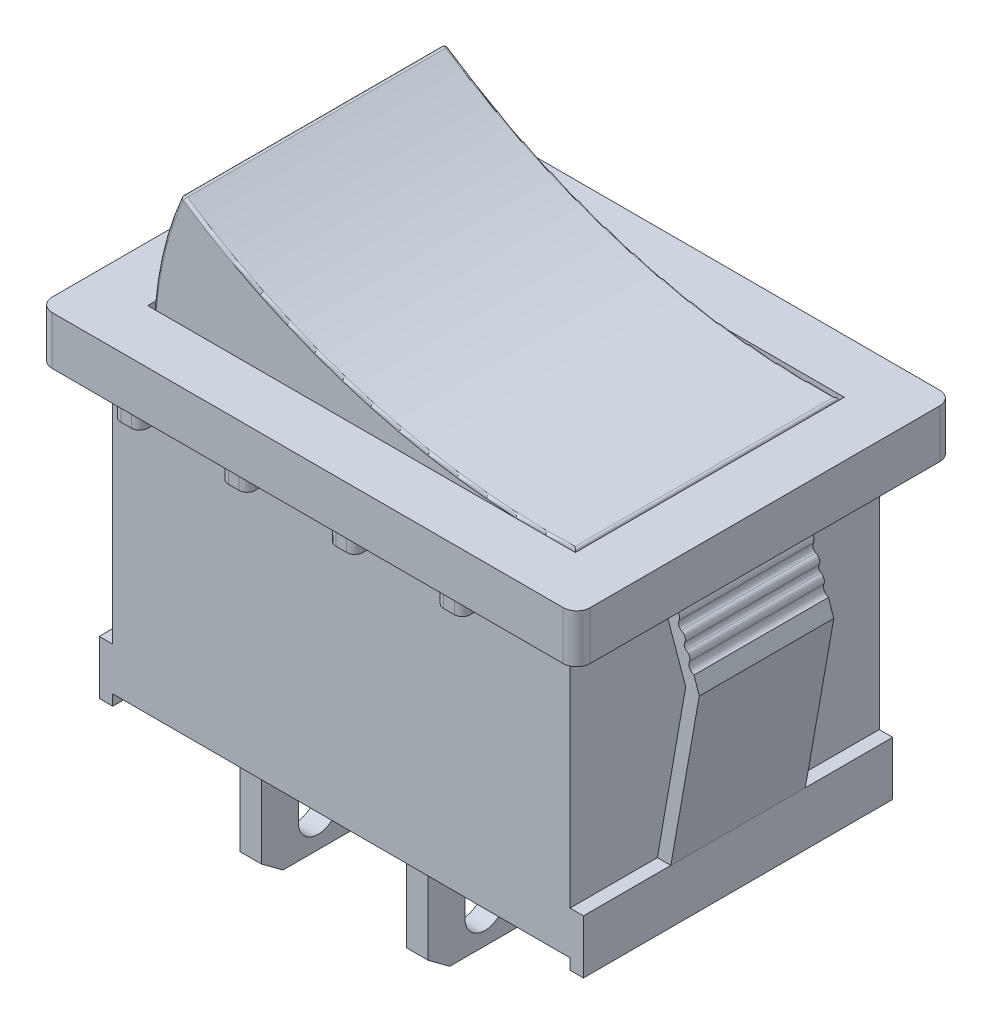
SolidWorks part; units mm, degrees
ref_plane "Front Plane" through (0, 0, 0) normal (0, 0, 1) x (1, 0, 0)
ref_plane "Top Plane" through (0, 0, 0) normal (0, 1, 0) x (1, 0, 0)
ref_plane "Right Plane" through (0, 0, 0) normal (1, 0, 0) x (0, 0, -1)
sketch "Sketch1" plane through (0, 0, 0) normal (0, 0, 1) x (1, 0, 0)
  line L0 (28.8419, 126.2682) -> (196.9257, 126.2682) construction
  line L1 (9.6613, 5.1642) -> (9.6613, 6.9336)
  line L2 (9.6613, 6.9336) -> (-9.9374, 6.9336)
  line L3 (-9.9374, 6.9336) -> (-9.9374, 5.1642)
  line L4 (-9.9374, 5.1642) -> (-8.8107, 5.1642)
  line L5 (-8.8107, 5.1642) -> (9.6613, 5.1642)
  line L6 (8.1893, 5.1642) -> (8.1893, -3.8358)
  line L7 (8.1893, -3.8358) -> (8.6893, -3.8358)
  line L8 (8.6893, -3.8358) -> (8.6893, -5.8358)
  line L9 (8.6893, -5.8358) -> (8.1893, -5.8358)
  line L10 (8.1893, -5.8358) -> (8.1893, -5.4358)
  line L11 (8.1893, -5.4358) -> (-8.8107, -5.4358)
  line L12 (-8.8107, -5.4358) -> (-8.8107, -5.8358)
  line L13 (-8.8107, -5.8358) -> (-9.3107, -5.8358)
  line L14 (-9.3107, -5.8358) -> (-9.3107, -3.8358)
  line L15 (-9.3107, -3.8358) -> (-8.8107, -3.8358)
  line L16 (-8.8107, -3.8358) -> (-8.8107, 5.1642)
  dimension "D1" = 0.5
  dimension "D2" = 2
  dimension "D3" = 0.4
  dimension "D4" = 9
  dimension "D5" = 17
extrude "Boss-Extrude1" add sketch "Sketch1" along normal blind 11.5 contours L16 L15 L14 L13 L12 L11 L10 L9 L8 L7 L6 L5
sketch "Sketch2" plane through (0, 5.1642, 0) normal (0, 1, 0) x (1, 0, 0)
  line L0 (8.1893, 0) -> (-8.8107, -11.5) construction
  line L1 (-8.8107, 0) -> (8.1893, -11.5) construction
  line L3 (9.6893, 1.25) -> (-10.3107, 1.25)
  line L4 (9.6893, 1.25) -> (9.6893, -12.75)
  line L5 (9.6893, -12.75) -> (-10.3107, -12.75)
  line L6 (-10.3107, 1.25) -> (-10.3107, -12.75)
  line L7 (9.6893, 1.25) -> (-10.3107, -12.75) construction
  line L8 (9.6893, -12.75) -> (-10.3107, 1.25) construction
  point P8 (-0.3107, -5.75)
  dimension "D1" = 20
  dimension "D2" = 14
extrude "Boss-Extrude2" add sketch "Sketch2" along normal blind 1.8
ref_plane "Plane1" through (0, 0, 8.25) normal (0, 0, 1) x (1, 0, 0)
sketch "Sketch3" plane through (0, 0, 8.25) normal (0, 0, 1) x (1, 0, 0)
  line L0 (102.0598, 373.3967) -> (564.7265, 373.3967) construction
  line L1 (8.1893, -3.8358) -> (8.6893, -3.8358)
  line L2 (8.6893, -3.8358) -> (9.7471, 2.1451)
  line L3 (9.7471, 2.1451) -> (9.5488, 2.7255)
  line L4 (8.7298, 5.1039) -> (8.7298, 5.1642)
  line L5 (-10.3107, 5.1642) -> (9.6893, 5.1642) construction
  line L6 (8.7298, 5.1642) -> (8.1893, 5.1642)
  line L7 (8.1893, 5.1642) -> (9.2413, 2.1928)
  line L8 (9.2413, 2.1928) -> (8.1893, -3.8358)
  line L9 (8.6893, -3.8358) -> (8.1893, -3.8358)
  line L10 (-8.8107, -3.8358) -> (-9.3107, -3.8358)
  line L11 (-9.3107, -3.8358) -> (-10.2811, 2.1451)
  line L12 (-10.2811, 2.1451) -> (-10.1179, 2.6658)
  line L13 (-9.403, 4.774) -> (-9.2478, 5.1642)
  line L14 (-9.2478, 5.1642) -> (-8.8107, 5.1642)
  line L15 (-8.8107, 5.1642) -> (-9.7685, 2.1928)
  line L16 (-9.7685, 2.1928) -> (-8.8107, -3.8358)
  arc A0 (9.5488, 2.7255) -> (9.3748, 3.062) centre (9.63, 2.9807) cw
  arc A1 (9.3748, 3.062) -> (9.2685, 3.3731) centre (9.166, 3.1644) ccw
  arc A2 (9.2685, 3.3731) -> (9.2154, 3.6229) centre (9.3668, 3.5245) cw
  arc A3 (9.2154, 3.6229) -> (9.0821, 3.9182) centre (9.001, 3.7039) ccw
  arc A4 (9.0821, 3.9182) -> (9.001, 4.2057) centre (9.1853, 4.1025) cw
  arc A5 (9.001, 4.2057) -> (8.8584, 4.5218) centre (8.7716, 4.2924) ccw
  arc A6 (8.8584, 4.5218) -> (8.8388, 4.8373) centre (9.0063, 4.6893) cw
  arc A7 (8.8388, 4.8373) -> (8.7298, 5.1039) centre (8.6267, 4.9061) ccw
  arc A8 (-10.1179, 2.6658) -> (-9.9427, 3.1176) centre (-10.2562, 2.9793) ccw
  arc A9 (-9.9427, 3.1176) -> (-9.746, 3.4104) centre (-9.6979, 3.1656) cw
  arc A10 (-9.746, 3.4104) -> (-9.746, 3.7039) centre (-9.8927, 3.5571) ccw
  arc A11 (-9.746, 3.7039) -> (-9.5582, 3.9706) centre (-9.5187, 3.7434) cw
  arc A12 (-9.5582, 3.9706) -> (-9.605, 4.2402) centre (-9.7164, 4.082) ccw
  arc A13 (-9.605, 4.2402) -> (-9.3775, 4.5218) centre (-9.1172, 4.0788) cw
  arc A14 (-9.3775, 4.5218) -> (-9.403, 4.774) centre (-9.4558, 4.6412) ccw
extrude "Boss-Extrude3" add sketch "Sketch3" against normal blind 5 contours A6 A7 L4 L6 L7 L8 L1 L2 L3 A0 A1 A2 A3 A4 A5 | L16 L10 L11 L12 A8 A9 A10 A11 A12 A13 A14 L13 L14 L15
ref_plane "Plane2" through (-7.7107, 0, 0) normal (1, 0, 0) x (0, 0, -1)
sketch "Sketch4" plane through (-7.7107, 0, 0) normal (1, 0, 0) x (0, 0, -1)
  line L0 (141.8895, 321.7559) -> (761.8895, 321.7559) construction
  line L1 (-14.9282, -5.3693) -> (5.7399, -5.3693) construction
  line L2 (-4.4696, -12.3753) -> (-3.6704, -11.7743)
  line L3 (-3.6704, -11.7743) -> (-3.6704, -6.7373)
  line L4 (-3.5841, -6.6693) -> (-3.4572, -6.6693)
  line L5 (-3.4572, -6.6693) -> (-3.4572, -5.3693)
  line L6 (-4.4696, -12.3753) -> (-7.0696, -12.3753)
  line L7 (-7.0696, -12.3753) -> (-7.8728, -11.7797)
  line L8 (-7.8728, -11.7797) -> (-7.8728, -6.7427)
  line L9 (-7.9422, -6.6693) -> (-8.0715, -6.6693)
  line L10 (-8.0715, -6.6693) -> (-8.0715, -5.3693)
  line L11 (-8.0715, -5.3693) -> (-3.4572, -5.3693)
  line L12 (-5.7598, -9.5912) -> (-5.7598, -11.1357) construction
  line L13 (-5.0181, -9.5912) -> (-5.0181, -11.1357)
  line L14 (-6.5016, -9.5912) -> (-6.5016, -11.1357)
  arc A0 (-3.6704, -6.7373) -> (-3.5841, -6.6693) centre (-3.5912, -6.749) cw
  arc A1 (-7.8728, -6.7427) -> (-7.9422, -6.6693) centre (-7.9442, -6.7407) ccw
  circle A2 centre (-5.7598, -7.0494) radius 0.9971
  arc A3 (-5.0181, -9.5912) -> (-6.5016, -9.5912) centre (-5.7598, -9.5912) ccw
  arc A4 (-6.5016, -11.1357) -> (-5.0181, -11.1357) centre (-5.7598, -11.1357) ccw
  point P22 (-5.7598, -10.3634)
  point P27 (-5.7598, -11.1357)
  dimension "D1" = 2.6
  dimension "D2" = 1
  dimension "D3" = 1
  dimension "D4" = 1.3
  dimension "D5" = 1.3
extrude "Boss-Extrude4" add sketch "Sketch4" along normal blind 0.8
pattern_linear "LPattern1" count 2 spacing 6.2 along (1, 0, 0) of "Boss-Extrude4"
sketch "Sketch5" plane through (0, 5.1642, 0) normal (0, -1, 0) x (1, 0, 0)
  line L0 (-8.3107, 11.5) -> (-8.3107, 11.7)
  line L1 (-8.8107, 11.5) -> (8.1893, 11.5) construction
  line L2 (-9.3107, 11.5) -> (-9.3107, 0) construction
  line L3 (-7.3107, 11.5) -> (-7.3107, 11.7)
  line L4 (-8.0107, 12) -> (-7.6107, 12)
  line L5 (-7.8107, 12) -> (-7.8107, 11.3092) construction
  line L6 (-8.3107, 11.5) -> (-7.3107, 11.5)
  arc A0 (-7.3107, 11.7) -> (-7.6107, 12) centre (-7.6107, 11.7) ccw
  arc A1 (-8.0107, 12) -> (-8.3107, 11.7) centre (-8.0107, 11.7) ccw
  dimension "D1" = 0.2
  dimension "D2" = 1
  dimension "D3" = 1
  dimension "D4" = 0.4
  dimension "D5" = 0.5
  dimension "D6" = 0.5
extrude "Boss-Extrude5" add sketch "Sketch5" along normal blind 1.2
pattern_linear "LPattern2" count 4 spacing 4 along (1, 0, 0) of "Boss-Extrude5"
sketch "Sketch6" plane through (0, 5.1642, 0) normal (0, -1, 0) x (1, 0, 0)
  line L2 (-0.3107, 5.75) -> (-13.9742, 5.75) construction
  line L3 (-13.9742, 5.75) -> (13.279, 5.75) construction
ref_plane "Plane3" through (0, 0, 5.75) normal (0, 0, 1) x (1, 0, 0)
mirror "Mirror1" about plane through (0, 0, 5.75) normal (0, 0, 1) of "LPattern2", "Boss-Extrude5"
sketch "Sketch7" plane through (0, 6.9642, 0) normal (0, 1, 0) x (1, 0, 0)
  line L0 (-10.3107, -12.75) -> (-0.3107, -5.75) construction
  line L1 (9.6893, 1.25) -> (-10.3107, 1.25) construction
  line L2 (8.1893, -10.75) -> (-8.8107, -10.75)
  line L3 (8.1893, -10.75) -> (8.1893, -0.75)
  line L4 (8.1893, -0.75) -> (-8.8107, -0.75)
  line L5 (-8.8107, -10.75) -> (-8.8107, -0.75)
  line L6 (8.1893, -10.75) -> (-8.8107, -0.75) construction
  line L7 (8.1893, -0.75) -> (-0.3107, -5.75) construction
  line L8 (-10.3107, 1.25) -> (-10.3107, -12.75) construction
  point P2 (-0.3107, -5.75)
  dimension "D1" = 2
  dimension "D2" = 1.5
extrude "Cut-Extrude1" cut sketch "Sketch7" against normal blind 1.5
ref_plane "Plane5" through (0, 0, 0.85) normal (0, 0, 1) x (1, 0, 0)
sketch "Sketch8" plane through (0, 0, 0.85) normal (0, 0, 1) x (1, 0, 0)
  line L0 (-10.3107, 5.1642) -> (-10.3107, 12.8273) construction
  line L1 (9.6893, 5.1642) -> (9.6893, 12.5473) construction
  line L2 (7.5893, 12.3514) -> (7.5893, 3.6168) construction
  line L3 (-8.2107, 12.3514) -> (-8.2107, 3.2529) construction
  line L4 (102.0213, 373.3251) -> (564.688, 373.3251) construction
  line L5 (10.0086, 6.9507) -> (10.0086, 5.4453) construction
  line L6 (10.0086, 5.4453) -> (-15.1054, 5.4453) construction
  line L7 (7.5393, 5.4453) -> (7.5393, 6.9642)
  line L8 (7.5393, 5.4453) -> (-8.1607, 5.4453)
  line L9 (-10.3107, 6.9642) -> (9.6893, 6.9642) construction
  arc A0 (-8.1607, 5.4453) -> (-7.0821, 11.0609) centre (4.4721, 5.9305) cw
  arc A1 (-7.0821, 11.0609) -> (7.5393, 6.9642) centre (6.4773, 31.3145) ccw
  point P22 (0, 0)
  point P25 (7.3979, 6.9507)
  dimension "D1" = 2.1
  dimension "D2" = 2.1
  dimension "D3" = 0.05
  dimension "D4" = 0.05
extrude "Boss-Extrude7" add sketch "Sketch8" along normal blind 9.8
sketch "Sketch9" plane through (-8.8107, 0, 0) normal (1, 0, 0) x (0, 0, -1)
  line L0 (-12.75, 6.9642) -> (1.25, 6.9642) construction
  line L1 (-11.0506, 6.9642) -> (-0.5378, 6.9642)
  line L2 (-11.0506, 6.9642) -> (-11.0506, 5.3154)
  line L3 (-11.0506, 5.3154) -> (-0.5378, 5.3154)
  line L4 (-0.5378, 6.9642) -> (-0.5378, 5.3154)
extrude "Boss-Extrude8" add sketch "Sketch9" along normal blind 0.55
sketch "Sketch10" plane through (8.1893, 0, 0) normal (-1, 0, 0) x (0, 0, 1)
  line L0 (-1.25, 6.9642) -> (12.75, 6.9642) construction
  line L1 (-0.2362, 6.9642) -> (11.7402, 6.9642)
  line L2 (-0.2362, 6.9642) -> (-0.2362, 5.2956)
  line L3 (-0.2362, 5.2956) -> (11.7402, 5.2956)
  line L4 (11.7402, 6.9642) -> (11.7402, 5.2956)
extrude "Boss-Extrude9" add sketch "Sketch10" along normal blind 0.55
fillet "Fillet1" radius 0.5 4 edges at (-10.3107, 6.0642, 12.75) (-10.3107, 6.0642, -1.25) (9.6893, 6.0642, -1.25) (9.6893, 6.0642, 12.75)
fillet "Fillet2" radius 0.1 6 edges at (-7.9413, 8.3242, 0.85) (-7.9413, 8.3242, 10.65) (-7.0821, 11.0609, 5.75) (-0.0986, 7.8449, 0.85) (7.5393, 6.9642, 5.75) (-0.0986, 7.8449, 10.65)
sketch "Sketch11" plane through (-8.8107, 0, 0) normal (1, 0, 0) x (0, 0, -1)
  line L0 (-0.6504, -5.4344) -> (0.3114, -5.4344) construction
  line L1 (-3.4572, -6.3328) -> (-3.4572, -4.6243) construction
  line L2 (-3.4572, -6.6693) -> (-3.4572, -5.4358) construction
  line L3 (0, -3.8358) -> (0, -5.8358) construction
  line L4 (-3.4572, -5.2549) -> (0, -5.2549)
  line L5 (-3.4572, -5.2549) -> (-3.4572, -5.5058)
  line L6 (-3.4572, -5.5058) -> (0, -5.5058)
  line L7 (0, -5.2549) -> (0, -5.5058)
  line L8 (-11.5, -5.8358) -> (0, -5.8358) construction
  dimension "D1" = 0.33
extrude "Boss-Extrude10" add sketch "Sketch11" along normal up to next
